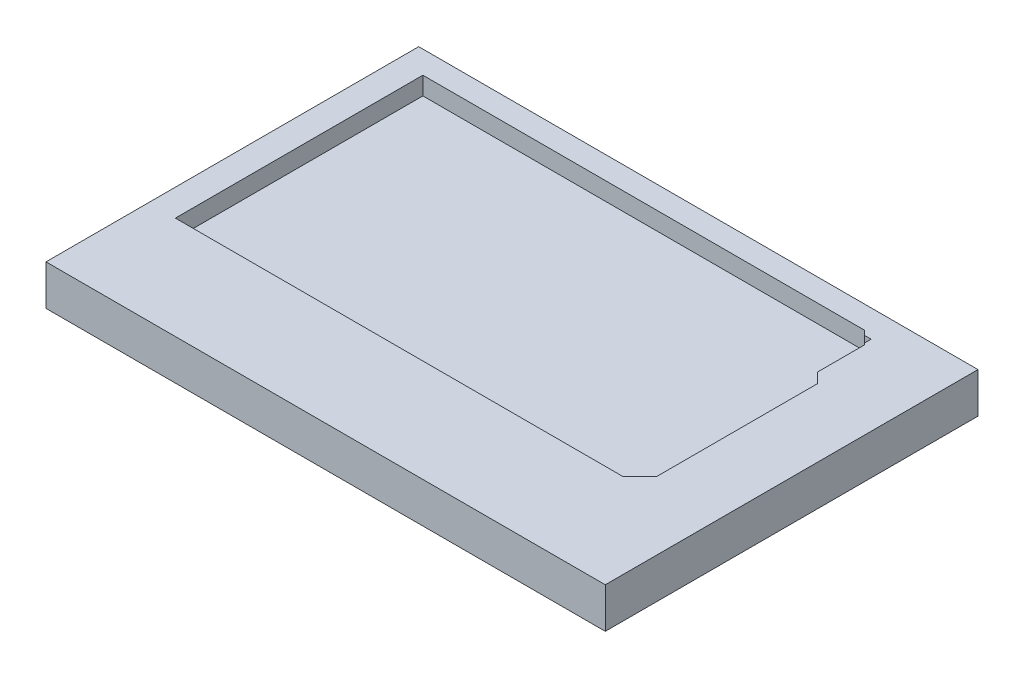
SolidWorks part; units mm, degrees
ref_plane "Front Plane" through (0, 0, 0) normal (0, 0, 1) x (1, 0, 0)
ref_plane "Top Plane" through (0, 0, 0) normal (0, 1, 0) x (1, 0, 0)
ref_plane "Right Plane" through (0, 0, 0) normal (1, 0, 0) x (0, 0, -1)
sketch "Sketch1" plane through (0, 0, 0) normal (0, 1, 0) x (1, 0, 0)
  line L1 (-50, -26.5) -> (50, -26.5)
  line L2 (-50, -26.5) -> (-50, 26.5)
  line L3 (-50, 26.5) -> (50, 26.5)
  line L4 (50, -26.5) -> (50, 26.5)
  line L5 (-50, -26.5) -> (50, 26.5) construction
  line L6 (-50, 26.5) -> (50, -26.5) construction
  point P0 (0, 0)
  dimension "D1" = 100
  dimension "D2" = 53
extrude "Boss-Extrude1" add sketch "Sketch1" along normal blind 5
sketch "Sketch2" plane through (0, 0, 0) normal (0, -1, 0) x (1, 0, 0)
  circle A0 centre (46.52, 24.173) radius 1.5875
  circle A1 centre (40.17, -24.087) radius 1.5875
  circle A2 centre (-34.76, -24.087) radius 1.5875
  circle A3 centre (-36.03, 24.173) radius 1.5875
extrude "Cut-Extrude1" cut sketch "Sketch2" against normal through all
sketch "Sketch3" plane through (0, 0, 0) normal (0, -1, 0) x (1, 0, 0)
  line L0 (50.3549, -14.1849) -> (52.6, -11.9398)
  line L1 (52.6, -11.9398) -> (52.6, 23.9522)
  line L2 (52.6, 23.9522) -> (48.8392, 27.713)
  line L3 (48.8392, 27.713) -> (-51, 27.713)
  line L4 (-51, 27.713) -> (-51, -27.5)
  line L5 (-51, -27.5) -> (47.4831, -27.5)
  line L6 (47.4831, -27.5) -> (50.3549, -24.6282)
  line L7 (50.3549, -24.6282) -> (50.3549, -14.1849)
  line L8 (49.3549, -13.7707) -> (51.6, -11.5256)
  line L9 (49.3549, -24.214) -> (49.3549, -13.7707)
  line L10 (47.0689, -26.5) -> (49.3549, -24.214)
  line L11 (-50, -26.5) -> (47.0689, -26.5)
  line L12 (-50, 26.713) -> (-50, -26.5)
  line L13 (48.425, 26.713) -> (-50, 26.713)
  line L14 (51.6, 23.538) -> (48.425, 26.713)
  line L15 (51.6, -11.5256) -> (51.6, 23.538)
  line L16 (49.3549, -13.7707) -> (51.6, -11.5256)
  line L17 (49.3549, -24.214) -> (49.3549, -13.7707)
  line L18 (47.0689, -26.5) -> (49.3549, -24.214)
  line L19 (-50, -26.5) -> (47.0689, -26.5)
  line L20 (-50, 26.713) -> (-50, -26.5)
  line L21 (48.425, 26.713) -> (-50, 26.713)
  line L22 (51.6, 23.538) -> (48.425, 26.713)
  line L23 (51.6, -11.5256) -> (51.6, 23.538)
  line L30 (-56.978, -32.5502) -> (67.7816, -32.5502)
  line L46 (-56.978, -32.5502) -> (-56.978, 50.5912)
  line L47 (-56.978, 50.5912) -> (67.7816, 50.5912)
  line L48 (67.7816, -32.5502) -> (67.7816, 50.5912)
  point P16 (0, 0)
  line M19 (50, -26.5) -> (50, 26.5)
  line M22 (-50, -26.5) -> (50, -26.5)
  dimension "D1" = 0
  dimension "D2" = 1
extrude "Boss-Extrude2" add sketch "Sketch3" against normal blind 9 contours L30 L48 L47 L46 L7 L6 L5 L4 L3 L2 L1 L0 M19 M22
sketch "Sketch4" plane through (0, 0, 0) normal (0, -1, 0) x (1, 0, 0)
  line L1 (-56.978, -32.5502) -> (67.7816, -32.5502)
  line L2 (-56.978, -32.5502) -> (-56.978, 50.5912)
  line L3 (-56.978, 50.5912) -> (67.7816, 50.5912)
  line L4 (67.7816, -32.5502) -> (67.7816, 50.5912)
extrude "Boss-Extrude3" add sketch "Sketch4" against normal blind 5
